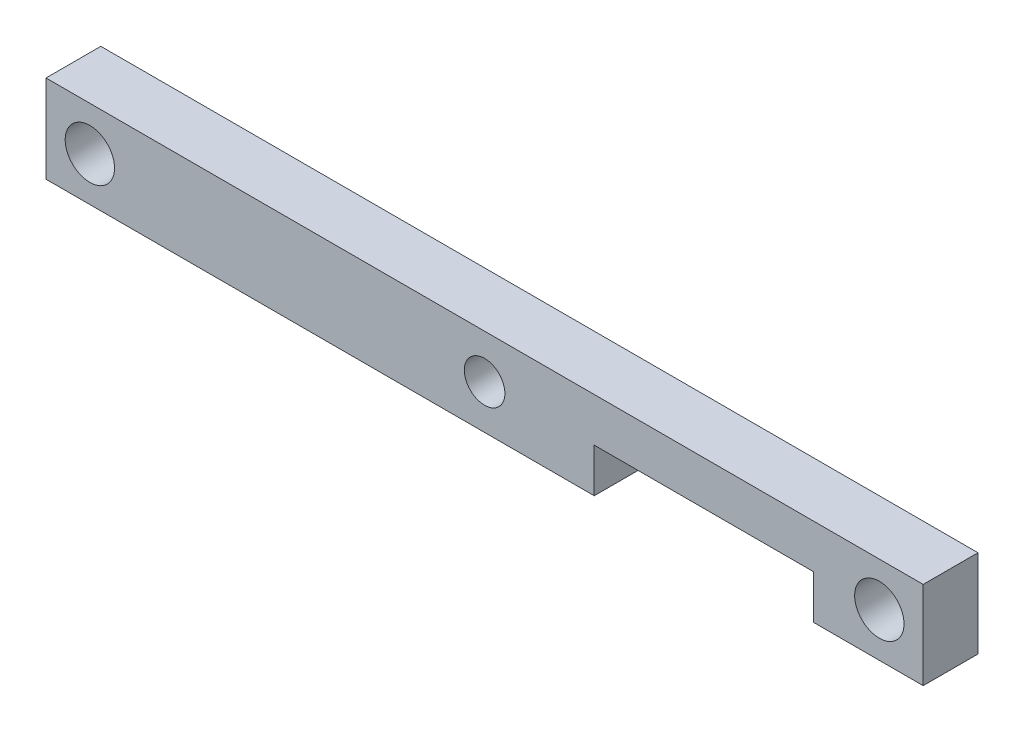
SolidWorks part; units mm, degrees
ref_plane "Piano frontale" through (0, 0, 0) normal (0, 0, 1) x (1, 0, 0)
ref_plane "Piano superiore" through (0, 0, 0) normal (0, 1, 0) x (1, 0, 0)
ref_plane "Piano destro" through (0, 0, 0) normal (1, 0, 0) x (0, 0, -1)
sketch "Schizzo1" plane through (0, 0, 0) normal (0, 0, 1) x (1, 0, 0)
  line L0 (-40, 0) -> (40, 0) construction
  line L1 (-40, 4) -> (40, 4)
  line L2 (-40, 4) -> (-40, -4)
  line L3 (-40, -4) -> (40, -4)
  line L4 (40, 4) -> (40, -4)
  circle A0 centre (-36, 0) radius 2.25
  circle A1 centre (0, 0) radius 1.85
  circle A2 centre (36, 0) radius 2.25
  dimension "D3" = 3.7
  dimension "D4" = 4.5
  dimension "D5" = 4.5
  dimension "D1" = 8
  dimension "D2" = 80
  dimension "D6" = 4
  dimension "D7" = 4
extrude "Estrusione-Estrusione1" add sketch "Schizzo1" along normal blind 5
sketch "Schizzo2" plane through (0, 0, 5) normal (0, 0, 1) x (1, 0, 0)
  line L0 (-40, -4) -> (40, -4) construction
  line L1 (10, -4) -> (30, -4)
  line L2 (10, -4) -> (10, 0)
  line L3 (10, 0) -> (30, 0)
  line L4 (30, -4) -> (30, 0)
  line L5 (40, 4) -> (-40, 4) construction
  line L6 (40, -4) -> (40, 4) construction
  dimension "D1" = 4
  dimension "D2" = 10
  dimension "D3" = 20
extrude "Taglio-Estrusione1" cut sketch "Schizzo2" against normal blind 8
